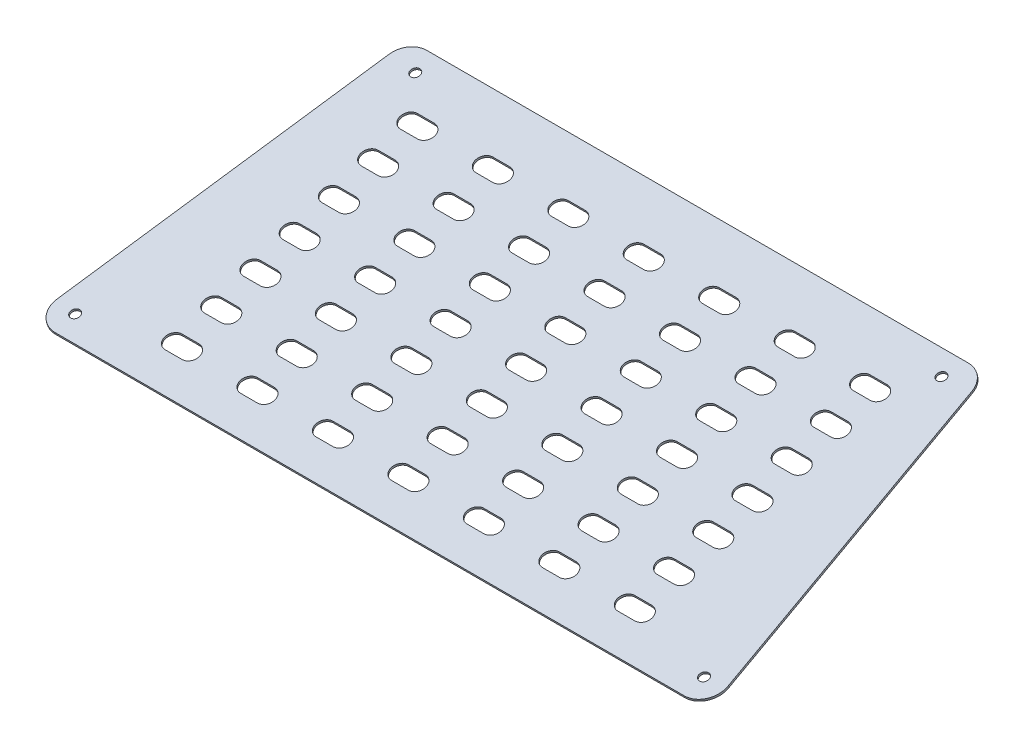
SolidWorks part; units mm, degrees
material "6061 Alloy"
ref_plane "Front Plane" through (0, 0, 0) normal (0, 0, 1) x (1, 0, 0)
ref_plane "Top Plane" through (0, 0, 0) normal (0, 1, 0) x (1, 0, 0)
ref_plane "Right Plane" through (0, 0, 0) normal (1, 0, 0) x (0, 0, -1)
ref_plane "Plane1" through (0, 394.1737, 122.8593) normal (0, 0.9547, 0.2976) x (1, 0, 0)
sketch "Sketch2" plane through (0, 394.1737, 122.8593) normal (0, 0.9547, 0.2976) x (1, 0, 0)
  line L0 (-135.8849, 895.8178) -> (-156.7709, 751.9303)
  line L1 (-146.8746, 740.4938) -> (153.3227, 740.4938)
  line L2 (163.219, 751.9303) -> (142.333, 895.8178)
  line L3 (132.4367, 904.3813) -> (-125.9886, 904.3813)
  line L4 (-176.7759, 725.4938) -> (-147.9064, 924.3813) construction
  line L6 (183.2241, 725.4938) -> (154.3545, 924.3813) construction
  line L7 (-185, 691.6928) -> (185, 691.6928) construction
  line L8 (154.3545, 924.3813) -> (-147.9064, 924.3813) construction
  line L9 (-184.7759, 725.4938) -> (191.2241, 725.4938) construction
  circle A0 centre (-122.3056, 894.7962) radius 2.25 construction
  circle A2 centre (-122.3056, 894.7962) radius 2.25
  circle A4 centre (128.7537, 894.7962) radius 2.25 construction
  circle A6 centre (128.7537, 894.7962) radius 2.25
  arc A8 (153.3227, 740.4938) -> (163.219, 751.9303) centre (153.3227, 750.4938) ccw
  arc A9 (142.333, 895.8178) -> (132.4367, 904.3813) centre (132.4367, 894.3813) ccw
  arc A10 (-135.8849, 895.8178) -> (-125.9886, 904.3813) centre (-125.9886, 894.3813) cw
  arc A11 (-156.7709, 751.9303) -> (-146.8746, 740.4938) centre (-146.8746, 750.4938) ccw
  circle A12 centre (153.2241, 750.4938) radius 2.25 construction
  circle A13 centre (153.2241, 750.4938) radius 2.25
  circle A14 centre (-146.7759, 750.4938) radius 2.25 construction
  circle A15 centre (-146.7759, 750.4938) radius 2.25
  point P2 (0, 0)
  point P5 (0, 0)
  point P12 (-128.1226, 869.0741)
  point P15 (0, 0)
  point P16 (-146.3526, 744.0895)
  point P18 (-158.7884, 703.6928)
  point P19 (0, 0)
  dimension "D5" = 10
  dimension "D1" = 15
  dimension "D2" = 20
  dimension "D3" = 16
  dimension "D4" = 16
extrude "Boss-Extrude1" add sketch "Sketch2" along normal blind 1 from surface at 1
sketch "Sketch3" plane through (0, 396.0831, 123.4545) normal (0, 0.9547, 0.2976) x (1, 0, 0)
  line L0 (-108.8491, 881.7813) -> (-100.8491, 881.7813)
  line L1 (-108.8491, 873.3813) -> (-100.8491, 873.3813)
  line L2 (132.4367, 904.3813) -> (-125.9886, 904.3813) construction
  line L3 (-135.8849, 895.8178) -> (-156.7709, 751.9303) construction
  line L4 (-72.8491, 881.7813) -> (-64.8491, 881.7813)
  line L5 (-72.8491, 873.3813) -> (-64.8491, 873.3813)
  line L6 (-36.8491, 881.7813) -> (-28.8491, 881.7813)
  line L7 (-36.8491, 873.3813) -> (-28.8491, 873.3813)
  line L8 (-0.8491, 881.7813) -> (7.1509, 881.7813)
  line L9 (-0.8491, 873.3813) -> (7.1509, 873.3813)
  line L10 (35.1509, 881.7813) -> (43.1509, 881.7813)
  line L11 (35.1509, 873.3813) -> (43.1509, 873.3813)
  line L12 (71.1509, 881.7813) -> (79.1509, 881.7813)
  line L13 (71.1509, 873.3813) -> (79.1509, 873.3813)
  line L14 (107.1509, 881.7813) -> (115.1509, 881.7813)
  line L15 (107.1509, 873.3813) -> (115.1509, 873.3813)
  line L16 (-72.8491, 862.1813) -> (-64.8491, 862.1813)
  line L17 (-72.8491, 853.7813) -> (-64.8491, 853.7813)
  line L18 (-36.8491, 862.1813) -> (-28.8491, 862.1813)
  line L19 (-36.8491, 853.7813) -> (-28.8491, 853.7813)
  line L20 (-0.8491, 862.1813) -> (7.1509, 862.1813)
  line L21 (-0.8491, 853.7813) -> (7.1509, 853.7813)
  line L22 (35.1509, 862.1813) -> (43.1509, 862.1813)
  line L23 (35.1509, 853.7813) -> (43.1509, 853.7813)
  line L24 (71.1509, 862.1813) -> (79.1509, 862.1813)
  line L25 (71.1509, 853.7813) -> (79.1509, 853.7813)
  line L26 (107.1509, 862.1813) -> (115.1509, 862.1813)
  line L27 (107.1509, 853.7813) -> (115.1509, 853.7813)
  line L28 (-72.8491, 842.5813) -> (-64.8491, 842.5813)
  line L29 (-72.8491, 834.1813) -> (-64.8491, 834.1813)
  line L30 (-36.8491, 842.5813) -> (-28.8491, 842.5813)
  line L31 (-36.8491, 834.1813) -> (-28.8491, 834.1813)
  line L32 (-0.8491, 842.5813) -> (7.1509, 842.5813)
  line L33 (-0.8491, 834.1813) -> (7.1509, 834.1813)
  line L34 (35.1509, 842.5813) -> (43.1509, 842.5813)
  line L35 (35.1509, 834.1813) -> (43.1509, 834.1813)
  line L36 (71.1509, 842.5813) -> (79.1509, 842.5813)
  line L37 (71.1509, 834.1813) -> (79.1509, 834.1813)
  line L38 (107.1509, 842.5813) -> (115.1509, 842.5813)
  line L39 (107.1509, 834.1813) -> (115.1509, 834.1813)
  line L40 (-72.8491, 822.9813) -> (-64.8491, 822.9813)
  line L41 (-72.8491, 814.5813) -> (-64.8491, 814.5813)
  line L42 (-36.8491, 822.9813) -> (-28.8491, 822.9813)
  line L43 (-36.8491, 814.5813) -> (-28.8491, 814.5813)
  line L44 (-0.8491, 822.9813) -> (7.1509, 822.9813)
  line L45 (-0.8491, 814.5813) -> (7.1509, 814.5813)
  line L46 (35.1509, 822.9813) -> (43.1509, 822.9813)
  line L47 (35.1509, 814.5813) -> (43.1509, 814.5813)
  line L48 (71.1509, 822.9813) -> (79.1509, 822.9813)
  line L49 (71.1509, 814.5813) -> (79.1509, 814.5813)
  line L50 (107.1509, 822.9813) -> (115.1509, 822.9813)
  line L51 (107.1509, 814.5813) -> (115.1509, 814.5813)
  line L52 (-72.8491, 803.3813) -> (-64.8491, 803.3813)
  line L53 (-72.8491, 794.9813) -> (-64.8491, 794.9813)
  line L54 (-36.8491, 803.3813) -> (-28.8491, 803.3813)
  line L55 (-36.8491, 794.9813) -> (-28.8491, 794.9813)
  line L56 (-0.8491, 803.3813) -> (7.1509, 803.3813)
  line L57 (-0.8491, 794.9813) -> (7.1509, 794.9813)
  line L58 (35.1509, 803.3813) -> (43.1509, 803.3813)
  line L59 (35.1509, 794.9813) -> (43.1509, 794.9813)
  line L60 (71.1509, 803.3813) -> (79.1509, 803.3813)
  line L61 (71.1509, 794.9813) -> (79.1509, 794.9813)
  line L62 (107.1509, 803.3813) -> (115.1509, 803.3813)
  line L63 (107.1509, 794.9813) -> (115.1509, 794.9813)
  line L64 (-72.8491, 783.7813) -> (-64.8491, 783.7813)
  line L65 (-72.8491, 775.3813) -> (-64.8491, 775.3813)
  line L66 (-36.8491, 783.7813) -> (-28.8491, 783.7813)
  line L67 (-36.8491, 775.3813) -> (-28.8491, 775.3813)
  line L68 (-0.8491, 783.7813) -> (7.1509, 783.7813)
  line L69 (-0.8491, 775.3813) -> (7.1509, 775.3813)
  line L70 (35.1509, 783.7813) -> (43.1509, 783.7813)
  line L71 (35.1509, 775.3813) -> (43.1509, 775.3813)
  line L72 (71.1509, 783.7813) -> (79.1509, 783.7813)
  line L73 (71.1509, 775.3813) -> (79.1509, 775.3813)
  line L74 (107.1509, 783.7813) -> (115.1509, 783.7813)
  line L75 (107.1509, 775.3813) -> (115.1509, 775.3813)
  line L76 (-72.8491, 764.1813) -> (-64.8491, 764.1813)
  line L77 (-72.8491, 755.7813) -> (-64.8491, 755.7813)
  line L78 (-36.8491, 764.1813) -> (-28.8491, 764.1813)
  line L79 (-36.8491, 755.7813) -> (-28.8491, 755.7813)
  line L80 (-0.8491, 764.1813) -> (7.1509, 764.1813)
  line L81 (-0.8491, 755.7813) -> (7.1509, 755.7813)
  line L82 (35.1509, 764.1813) -> (43.1509, 764.1813)
  line L83 (35.1509, 755.7813) -> (43.1509, 755.7813)
  line L84 (71.1509, 764.1813) -> (79.1509, 764.1813)
  line L85 (71.1509, 755.7813) -> (79.1509, 755.7813)
  line L86 (107.1509, 764.1813) -> (115.1509, 764.1813)
  line L87 (107.1509, 755.7813) -> (115.1509, 755.7813)
  line L88 (-108.8491, 862.1813) -> (-100.8491, 862.1813)
  line L89 (-108.8491, 853.7813) -> (-100.8491, 853.7813)
  line L90 (-108.8491, 842.5813) -> (-100.8491, 842.5813)
  line L91 (-108.8491, 834.1813) -> (-100.8491, 834.1813)
  line L92 (-108.8491, 822.9813) -> (-100.8491, 822.9813)
  line L93 (-108.8491, 814.5813) -> (-100.8491, 814.5813)
  line L94 (-108.8491, 803.3813) -> (-100.8491, 803.3813)
  line L95 (-108.8491, 794.9813) -> (-100.8491, 794.9813)
  line L96 (-108.8491, 783.7813) -> (-100.8491, 783.7813)
  line L97 (-108.8491, 775.3813) -> (-100.8491, 775.3813)
  line L98 (-108.8491, 764.1813) -> (-100.8491, 764.1813)
  line L99 (-108.8491, 755.7813) -> (-100.8491, 755.7813)
  arc A0 (-100.8491, 873.3813) -> (-100.8491, 881.7813) centre (-100.8491, 877.5813) ccw
  arc A1 (-108.8491, 881.7813) -> (-108.8491, 873.3813) centre (-108.8491, 877.5813) ccw
  arc A2 (-64.8491, 873.3813) -> (-64.8491, 881.7813) centre (-64.8491, 877.5813) ccw
  arc A3 (-72.8491, 881.7813) -> (-72.8491, 873.3813) centre (-72.8491, 877.5813) ccw
  arc A4 (-28.8491, 873.3813) -> (-28.8491, 881.7813) centre (-28.8491, 877.5813) ccw
  arc A5 (-36.8491, 881.7813) -> (-36.8491, 873.3813) centre (-36.8491, 877.5813) ccw
  arc A6 (7.1509, 873.3813) -> (7.1509, 881.7813) centre (7.1509, 877.5813) ccw
  arc A7 (-0.8491, 881.7813) -> (-0.8491, 873.3813) centre (-0.8491, 877.5813) ccw
  arc A8 (43.1509, 873.3813) -> (43.1509, 881.7813) centre (43.1509, 877.5813) ccw
  arc A9 (35.1509, 881.7813) -> (35.1509, 873.3813) centre (35.1509, 877.5813) ccw
  arc A10 (79.1509, 873.3813) -> (79.1509, 881.7813) centre (79.1509, 877.5813) ccw
  arc A11 (71.1509, 881.7813) -> (71.1509, 873.3813) centre (71.1509, 877.5813) ccw
  arc A12 (115.1509, 873.3813) -> (115.1509, 881.7813) centre (115.1509, 877.5813) ccw
  arc A13 (107.1509, 881.7813) -> (107.1509, 873.3813) centre (107.1509, 877.5813) ccw
  arc A14 (-64.8491, 853.7813) -> (-64.8491, 862.1813) centre (-64.8491, 857.9813) ccw
  arc A15 (-72.8491, 862.1813) -> (-72.8491, 853.7813) centre (-72.8491, 857.9813) ccw
  arc A16 (-28.8491, 853.7813) -> (-28.8491, 862.1813) centre (-28.8491, 857.9813) ccw
  arc A17 (-36.8491, 862.1813) -> (-36.8491, 853.7813) centre (-36.8491, 857.9813) ccw
  arc A18 (7.1509, 853.7813) -> (7.1509, 862.1813) centre (7.1509, 857.9813) ccw
  arc A19 (-0.8491, 862.1813) -> (-0.8491, 853.7813) centre (-0.8491, 857.9813) ccw
  arc A20 (43.1509, 853.7813) -> (43.1509, 862.1813) centre (43.1509, 857.9813) ccw
  arc A21 (35.1509, 862.1813) -> (35.1509, 853.7813) centre (35.1509, 857.9813) ccw
  arc A22 (79.1509, 853.7813) -> (79.1509, 862.1813) centre (79.1509, 857.9813) ccw
  arc A23 (71.1509, 862.1813) -> (71.1509, 853.7813) centre (71.1509, 857.9813) ccw
  arc A24 (115.1509, 853.7813) -> (115.1509, 862.1813) centre (115.1509, 857.9813) ccw
  arc A25 (107.1509, 862.1813) -> (107.1509, 853.7813) centre (107.1509, 857.9813) ccw
  arc A26 (-64.8491, 834.1813) -> (-64.8491, 842.5813) centre (-64.8491, 838.3813) ccw
  arc A27 (-72.8491, 842.5813) -> (-72.8491, 834.1813) centre (-72.8491, 838.3813) ccw
  arc A28 (-28.8491, 834.1813) -> (-28.8491, 842.5813) centre (-28.8491, 838.3813) ccw
  arc A29 (-36.8491, 842.5813) -> (-36.8491, 834.1813) centre (-36.8491, 838.3813) ccw
  arc A30 (7.1509, 834.1813) -> (7.1509, 842.5813) centre (7.1509, 838.3813) ccw
  arc A31 (-0.8491, 842.5813) -> (-0.8491, 834.1813) centre (-0.8491, 838.3813) ccw
  arc A32 (43.1509, 834.1813) -> (43.1509, 842.5813) centre (43.1509, 838.3813) ccw
  arc A33 (35.1509, 842.5813) -> (35.1509, 834.1813) centre (35.1509, 838.3813) ccw
  arc A34 (79.1509, 834.1813) -> (79.1509, 842.5813) centre (79.1509, 838.3813) ccw
  arc A35 (71.1509, 842.5813) -> (71.1509, 834.1813) centre (71.1509, 838.3813) ccw
  arc A36 (115.1509, 834.1813) -> (115.1509, 842.5813) centre (115.1509, 838.3813) ccw
  arc A37 (107.1509, 842.5813) -> (107.1509, 834.1813) centre (107.1509, 838.3813) ccw
  arc A38 (-64.8491, 814.5813) -> (-64.8491, 822.9813) centre (-64.8491, 818.7813) ccw
  arc A39 (-72.8491, 822.9813) -> (-72.8491, 814.5813) centre (-72.8491, 818.7813) ccw
  arc A40 (-28.8491, 814.5813) -> (-28.8491, 822.9813) centre (-28.8491, 818.7813) ccw
  arc A41 (-36.8491, 822.9813) -> (-36.8491, 814.5813) centre (-36.8491, 818.7813) ccw
  arc A42 (7.1509, 814.5813) -> (7.1509, 822.9813) centre (7.1509, 818.7813) ccw
  arc A43 (-0.8491, 822.9813) -> (-0.8491, 814.5813) centre (-0.8491, 818.7813) ccw
  arc A44 (43.1509, 814.5813) -> (43.1509, 822.9813) centre (43.1509, 818.7813) ccw
  arc A45 (35.1509, 822.9813) -> (35.1509, 814.5813) centre (35.1509, 818.7813) ccw
  arc A46 (79.1509, 814.5813) -> (79.1509, 822.9813) centre (79.1509, 818.7813) ccw
  arc A47 (71.1509, 822.9813) -> (71.1509, 814.5813) centre (71.1509, 818.7813) ccw
  arc A48 (115.1509, 814.5813) -> (115.1509, 822.9813) centre (115.1509, 818.7813) ccw
  arc A49 (107.1509, 822.9813) -> (107.1509, 814.5813) centre (107.1509, 818.7813) ccw
  arc A50 (-64.8491, 794.9813) -> (-64.8491, 803.3813) centre (-64.8491, 799.1813) ccw
  arc A51 (-72.8491, 803.3813) -> (-72.8491, 794.9813) centre (-72.8491, 799.1813) ccw
  arc A52 (-28.8491, 794.9813) -> (-28.8491, 803.3813) centre (-28.8491, 799.1813) ccw
  arc A53 (-36.8491, 803.3813) -> (-36.8491, 794.9813) centre (-36.8491, 799.1813) ccw
  arc A54 (7.1509, 794.9813) -> (7.1509, 803.3813) centre (7.1509, 799.1813) ccw
  arc A55 (-0.8491, 803.3813) -> (-0.8491, 794.9813) centre (-0.8491, 799.1813) ccw
  arc A56 (43.1509, 794.9813) -> (43.1509, 803.3813) centre (43.1509, 799.1813) ccw
  arc A57 (35.1509, 803.3813) -> (35.1509, 794.9813) centre (35.1509, 799.1813) ccw
  arc A58 (79.1509, 794.9813) -> (79.1509, 803.3813) centre (79.1509, 799.1813) ccw
  arc A59 (71.1509, 803.3813) -> (71.1509, 794.9813) centre (71.1509, 799.1813) ccw
  arc A60 (115.1509, 794.9813) -> (115.1509, 803.3813) centre (115.1509, 799.1813) ccw
  arc A61 (107.1509, 803.3813) -> (107.1509, 794.9813) centre (107.1509, 799.1813) ccw
  arc A62 (-64.8491, 775.3813) -> (-64.8491, 783.7813) centre (-64.8491, 779.5813) ccw
  arc A63 (-72.8491, 783.7813) -> (-72.8491, 775.3813) centre (-72.8491, 779.5813) ccw
  arc A64 (-28.8491, 775.3813) -> (-28.8491, 783.7813) centre (-28.8491, 779.5813) ccw
  arc A65 (-36.8491, 783.7813) -> (-36.8491, 775.3813) centre (-36.8491, 779.5813) ccw
  arc A66 (7.1509, 775.3813) -> (7.1509, 783.7813) centre (7.1509, 779.5813) ccw
  arc A67 (-0.8491, 783.7813) -> (-0.8491, 775.3813) centre (-0.8491, 779.5813) ccw
  arc A68 (43.1509, 775.3813) -> (43.1509, 783.7813) centre (43.1509, 779.5813) ccw
  arc A69 (35.1509, 783.7813) -> (35.1509, 775.3813) centre (35.1509, 779.5813) ccw
  arc A70 (79.1509, 775.3813) -> (79.1509, 783.7813) centre (79.1509, 779.5813) ccw
  arc A71 (71.1509, 783.7813) -> (71.1509, 775.3813) centre (71.1509, 779.5813) ccw
  arc A72 (115.1509, 775.3813) -> (115.1509, 783.7813) centre (115.1509, 779.5813) ccw
  arc A73 (107.1509, 783.7813) -> (107.1509, 775.3813) centre (107.1509, 779.5813) ccw
  arc A74 (-64.8491, 755.7813) -> (-64.8491, 764.1813) centre (-64.8491, 759.9813) ccw
  arc A75 (-72.8491, 764.1813) -> (-72.8491, 755.7813) centre (-72.8491, 759.9813) ccw
  arc A76 (-28.8491, 755.7813) -> (-28.8491, 764.1813) centre (-28.8491, 759.9813) ccw
  arc A77 (-36.8491, 764.1813) -> (-36.8491, 755.7813) centre (-36.8491, 759.9813) ccw
  arc A78 (7.1509, 755.7813) -> (7.1509, 764.1813) centre (7.1509, 759.9813) ccw
  arc A79 (-0.8491, 764.1813) -> (-0.8491, 755.7813) centre (-0.8491, 759.9813) ccw
  arc A80 (43.1509, 755.7813) -> (43.1509, 764.1813) centre (43.1509, 759.9813) ccw
  arc A81 (35.1509, 764.1813) -> (35.1509, 755.7813) centre (35.1509, 759.9813) ccw
  arc A82 (79.1509, 755.7813) -> (79.1509, 764.1813) centre (79.1509, 759.9813) ccw
  arc A83 (71.1509, 764.1813) -> (71.1509, 755.7813) centre (71.1509, 759.9813) ccw
  arc A84 (115.1509, 755.7813) -> (115.1509, 764.1813) centre (115.1509, 759.9813) ccw
  arc A85 (107.1509, 764.1813) -> (107.1509, 755.7813) centre (107.1509, 759.9813) ccw
  arc A86 (-100.8491, 853.7813) -> (-100.8491, 862.1813) centre (-100.8491, 857.9813) ccw
  arc A87 (-108.8491, 862.1813) -> (-108.8491, 853.7813) centre (-108.8491, 857.9813) ccw
  arc A88 (-100.8491, 834.1813) -> (-100.8491, 842.5813) centre (-100.8491, 838.3813) ccw
  arc A89 (-108.8491, 842.5813) -> (-108.8491, 834.1813) centre (-108.8491, 838.3813) ccw
  arc A90 (-100.8491, 814.5813) -> (-100.8491, 822.9813) centre (-100.8491, 818.7813) ccw
  arc A91 (-108.8491, 822.9813) -> (-108.8491, 814.5813) centre (-108.8491, 818.7813) ccw
  arc A92 (-100.8491, 794.9813) -> (-100.8491, 803.3813) centre (-100.8491, 799.1813) ccw
  arc A93 (-108.8491, 803.3813) -> (-108.8491, 794.9813) centre (-108.8491, 799.1813) ccw
  arc A94 (-100.8491, 775.3813) -> (-100.8491, 783.7813) centre (-100.8491, 779.5813) ccw
  arc A95 (-108.8491, 783.7813) -> (-108.8491, 775.3813) centre (-108.8491, 779.5813) ccw
  arc A96 (-100.8491, 755.7813) -> (-100.8491, 764.1813) centre (-100.8491, 759.9813) ccw
  arc A97 (-108.8491, 764.1813) -> (-108.8491, 755.7813) centre (-108.8491, 759.9813) ccw
  dimension "D1" = 8.4
  dimension "D2" = 8.4
  dimension "D5" = 29.375
  dimension "D3" = 8
  dimension "D4" = 22.6
  dimension "D6" = 7
  dimension "D7" = 7
extrude "Cut-Extrude1" cut sketch "Sketch3" against normal blind 1
sketch "Sketch4" plane through (0, 395.1284, 123.1569) normal (0, -0.9547, -0.2976) x (1, 0, 0)
  circle A0 centre (102.7241, -858.5387) radius 4 construction
  circle A1 centre (102.7241, -858.5387) radius 4
  circle A2 centre (102.7241, -799.5387) radius 4 construction
  circle A3 centre (102.7241, -799.5387) radius 4
  circle A4 centre (-96.2759, -799.5387) radius 4 construction
  circle A5 centre (-96.2759, -799.5387) radius 4
  circle A6 centre (-96.2759, -858.5387) radius 4 construction
  circle A7 centre (-96.2759, -858.5387) radius 4
extrude "Cut-Extrude2" [suppressed] cut sketch "Sketch4" against normal blind 10
